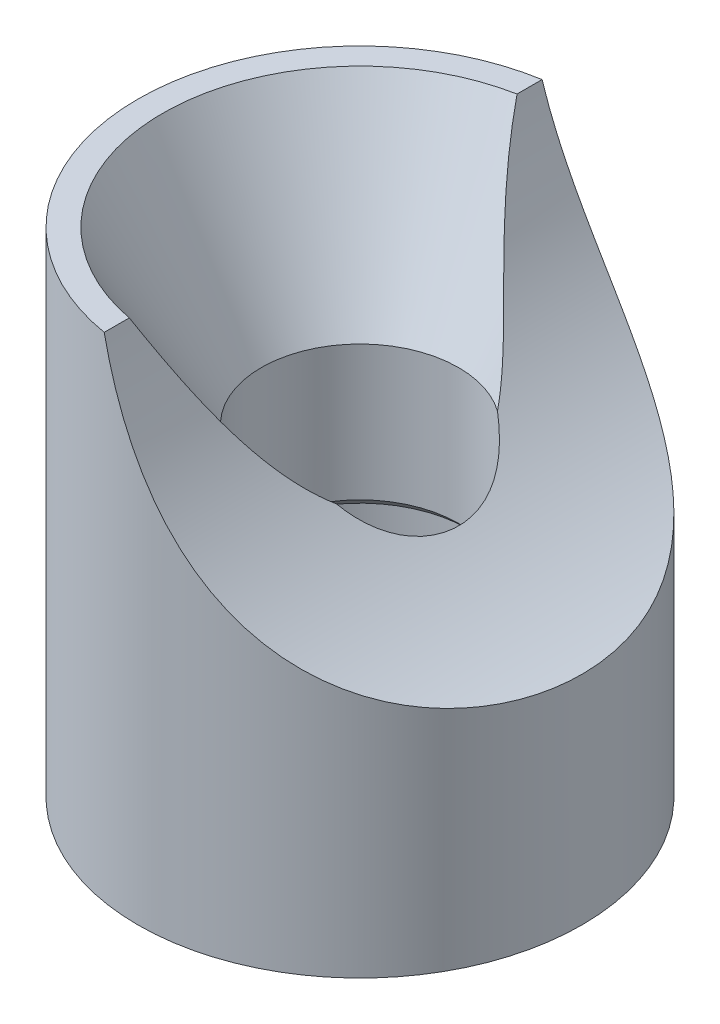
SolidWorks part; units mm, degrees
ref_plane "Front Plane" through (0, 0, 0) normal (0, 0, 1) x (1, 0, 0)
ref_plane "Top Plane" through (0, 0, 0) normal (0, 1, 0) x (1, 0, 0)
ref_plane "Right Plane" through (0, 0, 0) normal (1, 0, 0) x (0, 0, -1)
sketch "Sketch1" plane through (0, 0, 0) normal (0, 1, 0) x (1, 0, 0)
  circle A0 centre (0, 0) radius 2
  circle A1 centre (0, 0) radius 4.5
  dimension "D1" = 9
  dimension "D2" = 4
extrude "Boss-Extrude1" add sketch "Sketch1" along normal blind 10
chamfer "Chamfer1" distance 2 angle 60 1 edges at (0, 10, 2)
sketch "Sketch2" plane through (0, 0, 0) normal (0, -1, 0) x (1, 0, 0)
  circle A0 centre (0, 0) radius 2.25
  dimension "D1" = 4.5
extrude "Cut-Extrude2" cut sketch "Sketch2" against normal blind 3.6
sketch "Sketch3" plane through (0, 0, 0) normal (0, 0, 1) x (1, 0, 0)
  circle A0 centre (7, 12) radius 8
  point P5 (7.0229, 1.0187)
  dimension "D3" = 16
  dimension "D1" = 7
  dimension "D2" = 12
extrude "Cut-Extrude3" cut sketch "Sketch3" against normal through all both and the other way through all
chamfer "Chamfer2" distance 0.2 angle 45 2 edges at (0, 0, -2.25) (0, 3.6, -2)
